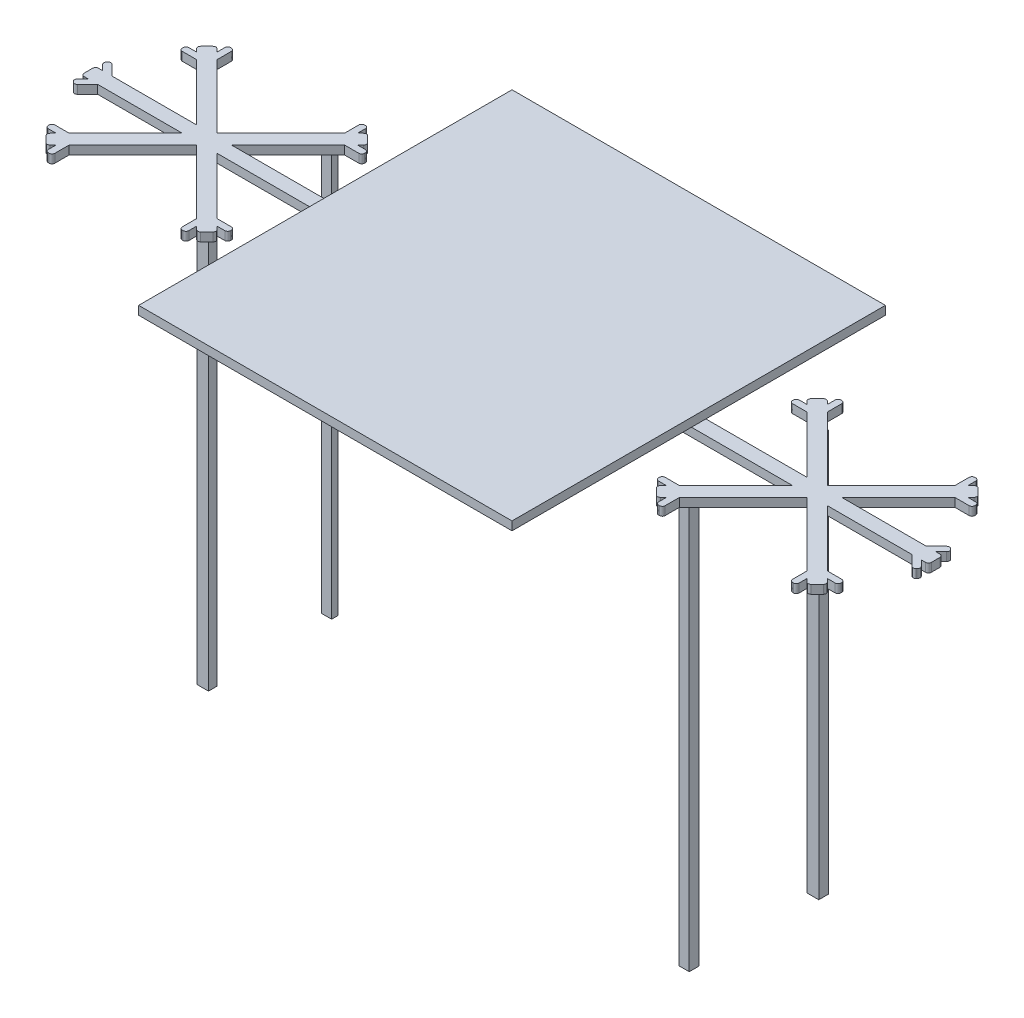
SolidWorks part; units mm, degrees
material "ABS"
ref_plane "Front" through (0, 0, 0) normal (0, 0, 1) x (1, 0, 0)
ref_plane "Top" through (0, 0, 0) normal (0, 1, 0) x (1, 0, 0)
ref_plane "Right" through (0, 0, 0) normal (1, 0, 0) x (0, 0, -1)
sketch "Sketch1" plane through (0, 0, 0) normal (0, 1, 0) x (1, 0, 0)
  line L1 (-65, -65) -> (65, -65)
  line L2 (-65, -65) -> (-65, 65)
  line L3 (-65, 65) -> (65, 65)
  line L4 (65, -65) -> (65, 65)
  line L5 (-65, -65) -> (65, 65) construction
  line L6 (-65, 65) -> (65, -65) construction
  point P0 (0, 0)
  dimension "D1" = 130
  dimension "D2" = 130
extrude "Boss-Extrude1" add sketch "Sketch1" along normal blind 3
sketch "Sketch2" plane through (0, 0, 0) normal (0, -1, 0) x (1, 0, 0)
  line L0 (-147.4984, 0.0016) -> (-141.774, 0.0016) construction
  line L1 (-147.5016, -2.4984) -> (-144.9984, -2.4984)
  line L3 (-147.5016, 2.5016) -> (-144.9984, 2.5016)
  line L4 (147.5016, -2.4984) -> (147.5016, 2.5016)
  line L5 (-130.7147, 28.0003) -> (-132.4825, 29.768)
  line L6 (107.9536, -1.8297) -> (107.9558, -1.8298) construction
  line L7 (-134.2503, 24.4647) -> (-136.018, 26.2325)
  line L9 (104.4822, 1.7678) -> (104.4854, 1.7709)
  line L10 (112.2871, 2.5016) -> (131.9725, 22.1869)
  line L11 (132.4825, 29.768) -> (136.018, 26.2325)
  line L17 (128.4369, 25.7225) -> (128.4369, 31.7225)
  line L18 (128.4369, 31.7225) -> (130.7147, 31.7225)
  line L19 (130.7147, 31.7225) -> (130.7147, 28.0003)
  line L20 (130.7147, 28.0003) -> (134.2503, 24.4647) construction
  line L21 (128.4369, 25.7225) -> (131.9725, 22.1869) construction
  line L22 (134.2503, 24.4647) -> (137.9725, 24.4647)
  line L23 (137.9725, 24.4647) -> (137.9725, 22.1869)
  line L24 (137.9725, 22.1869) -> (131.9725, 22.1869)
  line L25 (0, 0) -> (0, -65) construction
  line L26 (65, -65) -> (-65, -65) construction
  line L27 (-141.774, 2.5016) -> (-112.2871, 2.5016)
  line L28 (141.774, 2.5016) -> (146.0166, 6.7442)
  line L29 (146.0166, 6.7442) -> (147.6289, 5.132)
  line L30 (147.6289, 5.132) -> (144.9984, 2.5016)
  line L31 (141.774, -2.4984) -> (146.0166, -6.7411)
  line L32 (146.0166, -6.7411) -> (147.6289, -5.1289)
  line L33 (147.6289, -5.1289) -> (144.9984, -2.4984)
  line L34 (144.9984, 2.5016) -> (144.9984, -2.4984) construction
  line L35 (141.774, 2.5016) -> (141.774, -2.4984) construction
  line L36 (74.5291, 22.1885) -> (80.5291, 22.1885)
  line L37 (74.5291, 24.4663) -> (74.5291, 22.1885)
  line L38 (78.2513, 24.4663) -> (74.5291, 24.4663)
  line L39 (81.7853, 31.7225) -> (81.7853, 28.0003)
  line L40 (84.0631, 25.7225) -> (84.0631, 31.7225)
  line L41 (84.0631, 31.7225) -> (81.7853, 31.7225)
  line L42 (100.2161, 2.5016) -> (80.5291, 22.1885)
  line L43 (80.0175, 29.768) -> (76.4835, 26.2341)
  line L46 (128.4369, -25.7193) -> (128.4369, -31.7193)
  line L47 (130.7147, -31.7193) -> (130.7147, -27.9971)
  line L48 (128.4369, -31.7193) -> (130.7147, -31.7193)
  line L49 (134.2519, -24.4632) -> (137.9725, -24.4616)
  line L50 (137.9725, -24.4616) -> (137.9725, -22.1837)
  line L51 (137.9725, -22.1837) -> (131.9725, -22.1837)
  line L52 (112.2871, -2.4984) -> (131.9725, -22.1837)
  line L53 (132.4825, -29.7649) -> (136.018, -26.2293)
  line L54 (-81.7853, 28.0003) -> (-80.0175, 29.768)
  line L55 (-78.2513, 24.4663) -> (-76.4835, 26.2341)
  line L56 (84.0631, -25.7193) -> (84.0631, -31.7193)
  line L57 (84.0631, -31.7193) -> (81.7853, -31.7193)
  line L58 (81.7853, -31.7193) -> (81.7853, -27.9971)
  line L59 (74.5291, -22.1853) -> (80.5291, -22.1853)
  line L60 (74.5291, -24.4632) -> (74.5291, -22.1853)
  line L61 (78.2513, -24.4632) -> (74.5291, -24.4632)
  line L62 (-78.2513, -24.4632) -> (-76.4835, -26.2309)
  line L63 (-81.7853, -27.9971) -> (-80.0175, -29.7649)
  line L64 (80.0175, -29.7649) -> (76.4835, -26.2309)
  line L65 (100.2161, -2.4984) -> (80.5291, -22.1853)
  line L66 (-141.774, 2.5016) -> (-141.774, -2.4984) construction
  line L67 (-144.9984, 2.5016) -> (-144.9984, -2.4984) construction
  line L68 (-130.7147, -27.9971) -> (-132.4825, -29.7649)
  line L69 (-128.4369, 25.7225) -> (-131.9725, 22.1869) construction
  line L70 (-130.7147, 28.0003) -> (-134.2503, 24.4647) construction
  line L72 (-100.2161, -2.4984) -> (-80.5291, -22.1853)
  line L73 (-80.0175, -29.7649) -> (-76.4835, -26.2309)
  line L74 (-106.25, -3.5324) -> (-84.0631, -25.7193)
  line L75 (141.774, 0.0016) -> (147.5016, 0.0016) construction
  line L76 (-78.2513, -24.4632) -> (-74.5291, -24.4632)
  line L77 (-74.5291, -24.4632) -> (-74.5291, -22.1853)
  line L78 (-74.5291, -22.1853) -> (-80.5291, -22.1853)
  line L79 (-81.7853, -31.7193) -> (-81.7853, -27.9971)
  line L80 (-84.0631, -31.7193) -> (-81.7853, -31.7193)
  line L81 (-84.0631, -25.7193) -> (-84.0631, -31.7193)
  line L82 (107.9536, 1.8297) -> (107.9558, 1.8298) construction
  line L83 (-106.25, -3.5324) -> (-128.4369, -25.7193)
  line L84 (-132.4825, -29.7649) -> (-136.018, -26.2293)
  line L85 (-112.2871, -2.4984) -> (-131.9725, -22.1837)
  line L86 (-137.9725, -22.1837) -> (-131.9725, -22.1837)
  line L87 (-137.9725, -24.4616) -> (-137.9725, -22.1837)
  line L88 (-134.2519, -24.4632) -> (-137.9725, -24.4616)
  line L89 (-128.4369, -31.7193) -> (-130.7147, -31.7193)
  line L90 (-130.7147, -31.7193) -> (-130.7147, -27.9971)
  line L91 (-128.4369, -25.7193) -> (-128.4369, -31.7193)
  line L93 (-106.25, 3.5355) -> (-84.0631, 25.7225)
  line L94 (-80.0175, 29.768) -> (-76.4835, 26.2341)
  line L95 (112.2871, -2.4984) -> (141.774, -2.4984)
  line L96 (-84.0631, 31.7225) -> (-81.7853, 31.7225)
  line L97 (-84.0631, 25.7225) -> (-84.0631, 31.7225)
  line L98 (-81.7853, 31.7225) -> (-81.7853, 28.0003)
  line L99 (-78.2513, 24.4663) -> (-74.5291, 24.4663)
  line L100 (-74.5291, 24.4663) -> (-74.5291, 22.1885)
  line L101 (-74.5291, 22.1885) -> (-80.5291, 22.1885)
  line L102 (-147.6289, -5.1289) -> (-144.9984, -2.4984)
  line L103 (-146.0166, -6.7411) -> (-147.6289, -5.1289)
  line L104 (-141.774, -2.4984) -> (-146.0166, -6.7411)
  line L105 (-147.6289, 5.132) -> (-144.9984, 2.5016)
  line L106 (-146.0166, 6.7442) -> (-147.6289, 5.132)
  line L107 (-141.774, 2.5016) -> (-146.0166, 6.7442)
  line L108 (-137.9725, 22.1869) -> (-131.9725, 22.1869)
  line L109 (-137.9725, 24.4647) -> (-137.9725, 22.1869)
  line L110 (-134.2503, 24.4647) -> (-137.9725, 24.4647)
  line L111 (-130.7147, 31.7225) -> (-130.7147, 28.0003)
  line L112 (-128.4369, 31.7225) -> (-130.7147, 31.7225)
  line L113 (-128.4369, 25.7225) -> (-128.4369, 31.7225)
  line L114 (-132.4825, 29.768) -> (-136.018, 26.2325)
  line L115 (106.25, -3.5324) -> (84.0631, -25.7193)
  line L116 (-134.2519, -24.4632) -> (-136.018, -26.2293)
  line L117 (106.25, -3.5324) -> (128.4369, -25.7193)
  line L118 (-141.774, -2.4984) -> (-112.2871, -2.4984)
  line L119 (-147.5016, -2.4984) -> (-147.5016, 2.5016)
  line L120 (81.7853, 28.0003) -> (80.0175, 29.768)
  line L121 (78.2513, 24.4663) -> (76.4835, 26.2341)
  line L122 (-112.2871, 2.5016) -> (-131.9725, 22.1869)
  line L123 (130.7147, 28.0003) -> (132.4825, 29.768)
  line L124 (-106.25, 3.5355) -> (-128.4369, 25.7225)
  line L125 (-100.2161, 2.5016) -> (100.2161, 2.5016)
  line L126 (-100.2161, 2.5016) -> (-80.5291, 22.1885)
  line L127 (134.2503, 24.4647) -> (136.018, 26.2325)
  line L128 (-100.2161, -2.4984) -> (100.2161, -2.4984)
  line L130 (106.25, 3.5355) -> (84.0631, 25.7225)
  line L131 (112.2871, 2.5016) -> (141.774, 2.5016)
  line L132 (106.25, 3.5355) -> (128.4369, 25.7225)
  line L133 (144.9984, 2.5016) -> (147.5016, 2.5016)
  line L134 (144.9984, -2.4984) -> (147.5016, -2.4984)
  line L135 (134.2519, -24.4632) -> (136.018, -26.2293)
  line L136 (130.7147, -27.9971) -> (132.4825, -29.7649)
  line L137 (78.2513, -24.4632) -> (76.4835, -26.2309)
  line L138 (81.7853, -27.9971) -> (80.0175, -29.7649)
  arc A4 (104.4854, 1.7709) -> (104.4822, 1.7678) centre (106.2516, 0.0016) ccw
  point P0 (0, 0)
  point P13 (106.2516, 0.0016)
  point P127 (-106.2516, 0.0016)
  line M45 (65, -65) -> (65, 65)
  line M47 (-65, 65) -> (-65, -65)
  dimension "D3" = 41.25
extrude "Boss-Extrude3" add sketch "Sketch2" along normal blind 3 contours L128 L125 M47 M45 | L138 L58 L57 L56 L115 L117 L46 L48 L47 L136 L53 L135 L49 L50 L51 L52 L95 L31 L32 L33 L134 L4 L133 L30 L29 L28 L131 L10 L24 L23 L22 L127 L11 L123 L19 L18 L17 L132 L130 L40 L41 L39 L120 L43 L121 L38 L37 L36 L42 L125 M45 | L72 L128 L125 L126 L101 L100 L99 L55 L94 L54 L98 L96 L97 L93 L124 L113 L112 L111 L5 L114 L7 L110 L109 L108 L122 L27 L107 L106 L105 L3 L119 L1 L102 L103 L104 L118 L85 L86 L87 L88 L116 L84 L68 L90 L89 L91 L83 L74 L81 L80 M47
fillet "Fillet1" radius 1 60 edges at (-74.5291, -1.5, -22.1853) (-74.5291, -1.5, -24.4632) (-76.4835, -1.5, -26.2309) (-80.0175, -1.5, -29.7649) (-81.7853, -1.5, -31.7193) (-84.0631, -1.5, -31.7193) (-74.5291, -1.5, 22.1885) (-74.5291, -1.5, 24.4663) (-76.4835, -1.5, 26.2341) (-80.0175, -1.5, 29.768) (-81.7853, -1.5, 31.7225) (-84.0631, -1.5, 31.7225) (-128.4369, -1.5, 31.7225) (-130.7147, -1.5, 31.7225) (-132.4825, -1.5, 29.768) (-136.018, -1.5, 26.2325) (-137.9725, -1.5, 22.1869) (-137.9725, -1.5, 24.4647) (-128.4369, -1.5, -31.7193) (-130.7147, -1.5, -31.7193) (-132.4825, -1.5, -29.7649) (-136.018, -1.5, -26.2293) (-137.9725, -1.5, -24.4616) (-137.9725, -1.5, -22.1837) (-146.0166, -1.5, 6.7442) (-147.6289, -1.5, 5.132) (-147.5016, -1.5, 2.5016) (-147.5016, -1.5, -2.4984) (-147.6289, -1.5, -5.1289) (-146.0166, -1.5, -6.7411) (84.0631, -1.5, -31.7193) (81.7853, -1.5, -31.7193) (80.0175, -1.5, -29.7649) (76.4835, -1.5, -26.2309) (74.5291, -1.5, -22.1853) (74.5291, -1.5, -24.4632) (74.5291, -1.5, 22.1885) (74.5291, -1.5, 24.4663) (76.4835, -1.5, 26.2341) (80.0175, -1.5, 29.768) (84.0631, -1.5, 31.7225) (81.7853, -1.5, 31.7225) (128.4369, -1.5, 31.7225) (130.7147, -1.5, 31.7225) (132.4825, -1.5, 29.768) (136.018, -1.5, 26.2325) (137.9725, -1.5, 24.4647) (137.9725, -1.5, 22.1869) (146.0166, -1.5, 6.7442) (147.6289, -1.5, 5.132) (147.5016, -1.5, 2.5016) (147.5016, -1.5, -2.4984) (147.6289, -1.5, -5.1289) (146.0166, -1.5, -6.7411) (137.9725, -1.5, -22.1837) (137.9725, -1.5, -24.4616) (136.018, -1.5, -26.2293) (132.4825, -1.5, -29.7649) (130.7147, -1.5, -31.7193) (128.4369, -1.5, -31.7193)
sketch "Sketch3" plane through (0, -3, 0) normal (0, -1, 0) x (1, 0, 0)
  line L20 (-100.2161, 2.5016) -> (-80.5291, 22.1885) construction
  line L27 (-86.4752, 23.1678) -> (-82.5095, 23.1678)
  line L28 (-86.4752, 23.1678) -> (-86.4752, 20.2082)
  line L29 (-86.4752, 20.2082) -> (-82.5095, 20.2082)
  line L30 (-82.5095, 23.1678) -> (-82.5095, 20.2082)
  line L31 (-86.4752, 23.1678) -> (-82.5095, 20.2082) construction
  line L32 (-86.4752, 20.2082) -> (-82.5095, 23.1678) construction
  line L33 (-100.2161, -2.4984) -> (-80.5291, -22.1853) construction
  line L34 (-86.2213, -22.1837) -> (-82.7617, -22.1837)
  line L35 (-86.2213, -22.1837) -> (-86.2213, -19.9528)
  line L36 (-86.2213, -19.9528) -> (-82.7617, -19.9528)
  line L37 (-82.7617, -22.1837) -> (-82.7617, -19.9528)
  line L38 (-86.2213, -22.1837) -> (-82.7617, -19.9528) construction
  line L39 (-86.2213, -19.9528) -> (-82.7617, -22.1837) construction
  line L40 (100.2161, -2.4984) -> (80.5291, -22.1853) construction
  line L41 (86.6426, -23.4993) -> (82.556, -23.4993)
  line L42 (86.6426, -23.4993) -> (86.6426, -20.1585)
  line L43 (86.6426, -20.1585) -> (82.556, -20.1585)
  line L44 (82.556, -23.4993) -> (82.556, -20.1585)
  line L45 (86.6426, -23.4993) -> (82.556, -20.1585) construction
  line L46 (86.6426, -20.1585) -> (82.556, -23.4993) construction
  line L48 (82.3092, 24.0897) -> (85.7911, 24.0897)
  line L49 (82.3092, 24.0897) -> (82.3092, 20.7509)
  line L50 (82.3092, 20.7509) -> (85.7911, 20.7509)
  line L51 (85.7911, 24.0897) -> (85.7911, 20.7509)
  line L52 (82.3092, 24.0897) -> (85.7911, 20.7509) construction
  line L53 (82.3092, 20.7509) -> (85.7911, 24.0897) construction
  point P24 (-84.4923, 21.688)
  point P31 (-84.4915, -21.0682)
  point P38 (84.5993, -21.8289)
  point P45 (84.0502, 22.4203)
extrude "Boss-Extrude4" add sketch "Sketch3" along normal blind 140
